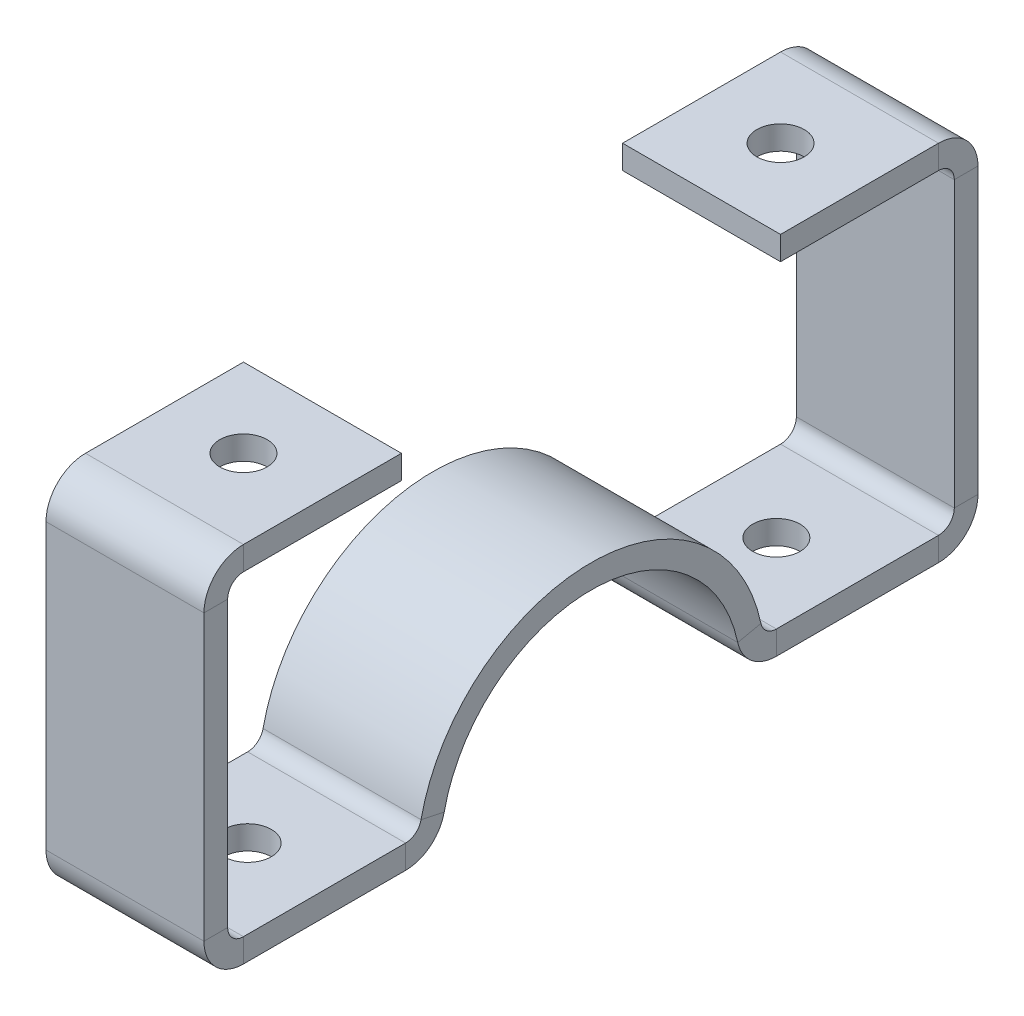
SolidWorks part; units mm, degrees
material "Galvanized Steel"
ref_plane "Front Plane" through (0, 0, 0) normal (0, 0, 1) x (1, 0, 0)
ref_plane "Top Plane" through (0, 0, 0) normal (0, 1, 0) x (1, 0, 0)
ref_plane "Right Plane" through (0, 0, 0) normal (1, 0, 0) x (0, 0, -1)
sketch "Sketch7" plane through (0, 0, 0) normal (1, 0, 0) x (0, 0, -1)
  line L11 (23.4734, 0) -> (44, 0)
  line L12 (-49, 46) -> (49, 46) construction
  line L13 (-49, 41) -> (-49, 5)
  line L14 (-44, 0) -> (-23.4734, 0)
  line L15 (49, 41) -> (49, 5)
  line L16 (-44, 46) -> (-24, 46)
  line L18 (24, 46) -> (44, 46)
  arc A7 (18.5831, 3.9583) -> (-18.5831, 3.9583) centre (0, 0) ccw
  arc A8 (44, 46) -> (49, 41) centre (44, 41) cw
  arc A9 (44, 0) -> (49, 5) centre (44, 5) ccw
  arc A10 (18.5831, 3.9583) -> (23.4734, 0) centre (23.4734, 5) ccw
  arc A11 (-18.5831, 3.9583) -> (-23.4734, 0) centre (-23.4734, 5) cw
  arc A12 (-49, 5) -> (-44, 0) centre (-44, 5) ccw
  arc A13 (-44, 46) -> (-49, 41) centre (-44, 41) ccw
  point P10 (0, 46)
  point P21 (19, 0)
  point P27 (-49, 0)
  point P31 (0, 7.0072)
  point P32 (0, 0)
  point P33 (0, 0)
  dimension "D1" = 46
  dimension "D5" = 5
  dimension "D6" = 20
  dimension "D3" = 38
  dimension "D2" = 48
ref_plane "Plane1" through (0, 0, 24) normal (0, 0, 1) x (1, 0, 0)
sketch "Sketch8" plane through (0, 0, 24) normal (0, 0, 1) x (1, 0, 0)
  line L1 (10, 46) -> (-10, 46)
  line L2 (10, 46) -> (10, 43)
  line L3 (10, 43) -> (-10, 43)
  line L4 (-10, 46) -> (-10, 43)
  dimension "D1" = 3
  dimension "D2" = 20
sweep "Sweep1" add profiles "Sketch8" path "Sketch7"
sketch "Sketch10" plane through (0, 3, 0) normal (0, 1, 0) x (1, 0, 0)
  line L0 (-10, -23.4734) -> (10, -23.4734) construction
  line L1 (-10, 23.4734) -> (10, 23.4734) construction
  circle A0 centre (0, 33.4734) radius 3
  circle A1 centre (0, -33.4734) radius 3
  point P12 (0, -23.4734)
  dimension "D1" = 6
  dimension "D2" = 6
  dimension "D4" = 10
  dimension "D3" = 10
extrude "Cut-Extrude1" cut sketch "Sketch10" against normal through all
sketch "Sketch11" plane through (0, 43, 0) normal (0, -1, 0) x (1, 0, 0)
  line L0 (-10, 24) -> (10, 24) construction
  line L1 (-10, -24) -> (10, -24) construction
  circle A0 centre (0, 34) radius 3
  circle A1 centre (0, -34) radius 3
  point P8 (0, 24)
  dimension "D1" = 10
  dimension "D3" = 6
  dimension "D4" = 6
  dimension "D2" = 10
extrude "Cut-Extrude2" cut sketch "Sketch11" against normal through all
